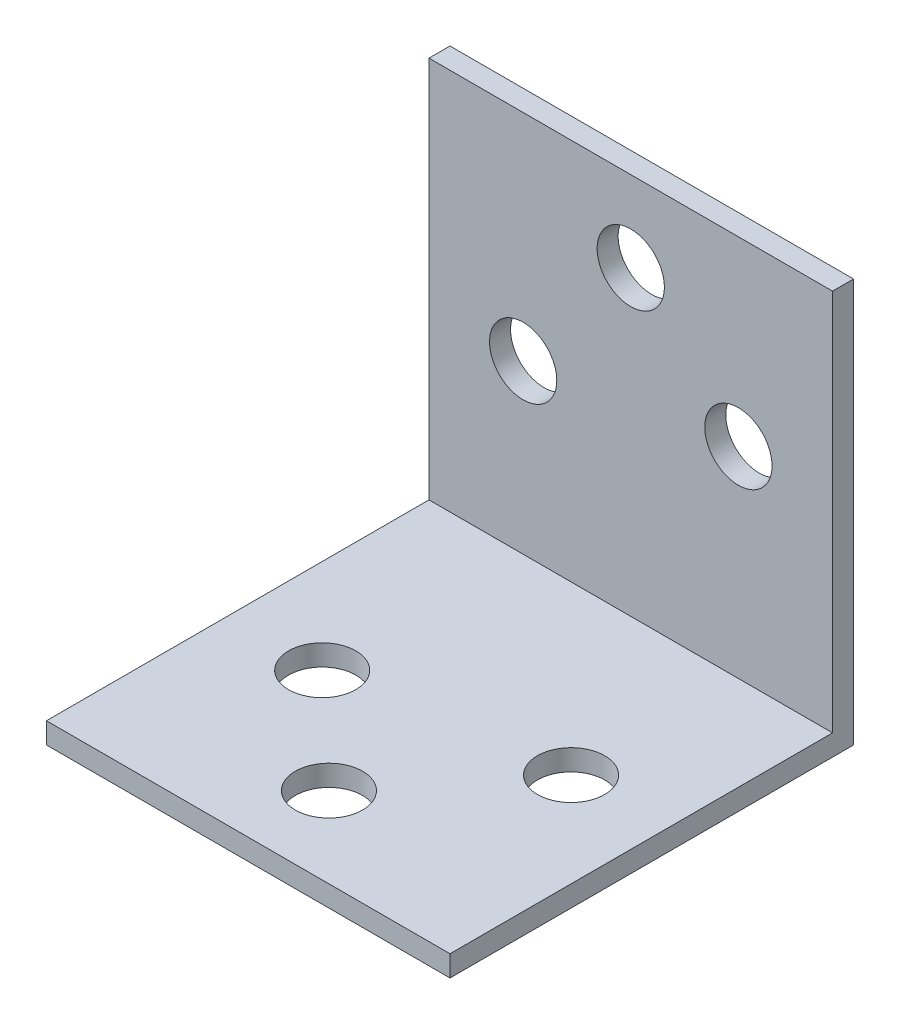
SolidWorks part; units mm, degrees
ref_plane "Front Plane" through (0, 0, 0) normal (0, 0, 1) x (1, 0, 0)
ref_plane "Top Plane" through (0, 0, 0) normal (0, 1, 0) x (1, 0, 0)
ref_plane "Right Plane" through (0, 0, 0) normal (1, 0, 0) x (0, 0, -1)
sketch "Sketch1" plane through (0, 0, 0) normal (0, 1, 0) x (1, 0, 0)
  line L0 (0, 0) -> (38.1, 0)
  line L1 (38.1, 0) -> (38.1, -38.1)
  line L3 (38.1, -38.1) -> (0, -38.1)
  line L5 (0, -38.1) -> (0, 0)
  circle A0 centre (19.05, -30.48) radius 3.175
  circle A1 centre (8.89, -20.955) radius 3.175
  circle A2 centre (29.21, -17.78) radius 3.175
  point P3 (19.05, 0)
  dimension "D5" = 6.35
  dimension "D1" = 38.1
  dimension "D2" = 38.1
  dimension "D3" = 7.62
  dimension "D4" = 8.89
  dimension "D6" = 17.145
  dimension "D7" = 8.89
  dimension "D8" = 20.32
extrude "Boss-Extrude1" add sketch "Sketch1" along normal blind 1.9844
sketch "Sketch2" plane through (0, 0, 0) normal (0, 0, 1) x (1, 0, 0)
  line L0 (0, 1.9844) -> (0, 38.1)
  line L2 (0, 38.1) -> (38.1, 38.1)
  line L4 (38.1, 38.1) -> (38.1, 1.9844)
  line L5 (38.1, 0) -> (0, 0) construction
  line L10 (0, 0) -> (38.1, 0)
  line L11 (0, 1.9844) -> (0, 0)
  line L12 (38.1, 1.9844) -> (0, 1.9844)
  line L13 (38.1, 0) -> (38.1, 1.9844)
  line L16 (38.1, 1.9844) -> (0, 1.9844)
  circle A0 centre (19.05, 30.48) radius 3.175
  circle A1 centre (8.89, 17.78) radius 3.175
  circle A2 centre (29.21, 20.955) radius 3.175
  point P4 (19.05, 38.1)
  point P7 (1.4013, 50.8)
  point P22 (0.7661, 50.8)
  dimension "D5" = 6.35
  dimension "D1" = 38.1
  dimension "D6" = 7.62
  dimension "D7" = 8.89
  dimension "D8" = 8.89
  dimension "D9" = 20.32
  dimension "D10" = 17.145
  dimension "D4" = 0
extrude "Boss-Extrude2" add sketch "Sketch2" along normal blind 1.9844
